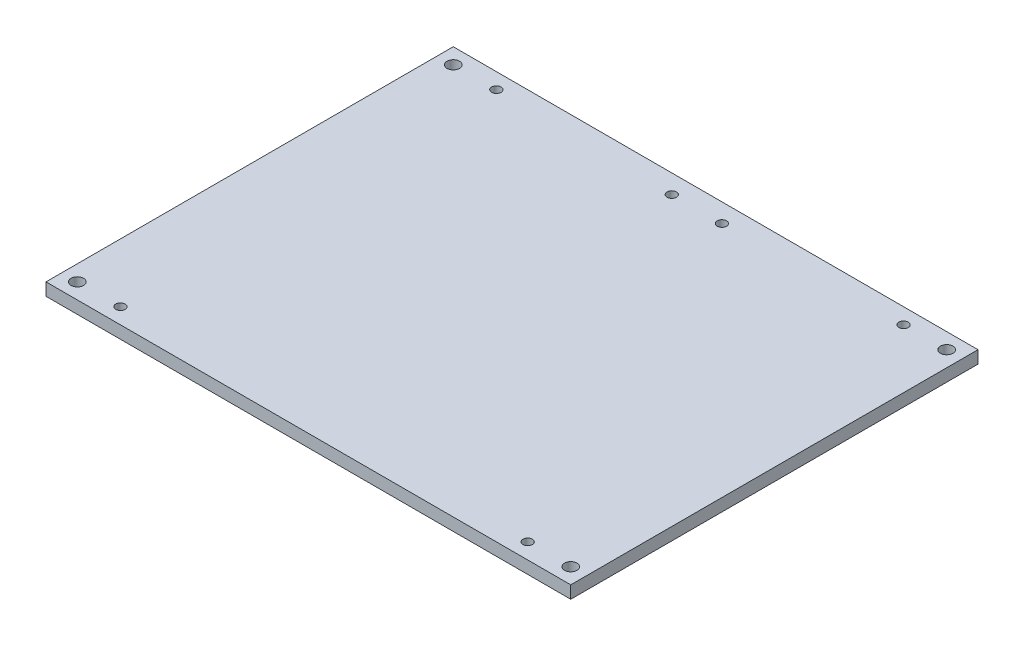
SolidWorks part; units mm, degrees
ref_plane "Front Plane" through (0, 0, 0) normal (0, 0, 1) x (1, 0, 0)
ref_plane "Top Plane" through (0, 0, 0) normal (0, 1, 0) x (1, 0, 0)
ref_plane "Right Plane" through (0, 0, 0) normal (1, 0, 0) x (0, 0, -1)
sketch "Sketch1" plane through (0, 0, 0) normal (0, 1, 0) x (1, 0, 0)
  line L1 (-83.75, 65) -> (83.75, 65)
  line L2 (-83.75, 65) -> (-83.75, -65)
  line L3 (-83.75, -65) -> (83.75, -65)
  line L4 (83.75, 65) -> (83.75, -65)
  line L5 (-83.75, 65) -> (83.75, -65) construction
  line L6 (-83.75, -65) -> (83.75, 65) construction
  point P0 (0, 0)
  dimension "D1" = 130
  dimension "D2" = 167.5
extrude "Boss-Extrude1" add sketch "Sketch1" along normal blind 4
sketch "Sketch2" plane through (0, 4, 0) normal (0, 1, 0) x (1, 0, 0)
  line L0 (-83.75, -65) -> (83.75, -65) construction
  line L1 (-65, 60) -> (65, 60) construction
  line L2 (-65, 60) -> (-65, -60) construction
  line L3 (-65, -60) -> (65, -60) construction
  line L4 (65, 60) -> (65, -60) construction
  line L5 (-65, 60) -> (65, -60) construction
  line L6 (-65, -60) -> (65, 60) construction
  circle A0 centre (-65, -60) radius 1.5
  circle A1 centre (65, -60) radius 1.5
  circle A2 centre (65, 60) radius 1.5
  circle A3 centre (-65, 60) radius 1.5
  point P0 (0, 0)
  dimension "D3" = 3
  dimension "D4" = 5
  dimension "D1" = 130
  dimension "D2" = 120
extrude "Cut-Extrude1" cut sketch "Sketch2" against normal blind 3
sketch "Sketch3" plane through (0, 4, 0) normal (0, 1, 0) x (1, 0, 0)
  line L0 (-8, 59) -> (8, 59) construction
  line L1 (83.75, 65) -> (-83.75, 65) construction
  circle A0 centre (-8, 59) radius 1.5
  circle A1 centre (8, 59) radius 1.5
  point P3 (0, 59)
  dimension "D2" = 3
  dimension "D1" = 16
  dimension "D3" = 6
extrude "Cut-Extrude2" cut sketch "Sketch3" against normal blind 3
sketch "Sketch4" plane through (0, 4, 0) normal (0, 1, 0) x (1, 0, 0)
  line L0 (-83.75, -65) -> (83.75, -65) construction
  line L1 (-30, 22) -> (30, 22)
  line L2 (-30, 22) -> (-30, 25)
  line L3 (-30, 25) -> (30, 25)
  line L4 (30, 22) -> (30, 25)
  line L5 (-30, -32) -> (30, -32)
  line L6 (-30, -32) -> (-30, -35)
  line L7 (-30, -35) -> (30, -35)
  line L8 (30, -32) -> (30, -35)
  point P8 (0, 22)
  dimension "D1" = 54
  dimension "D2" = 3
  dimension "D3" = 30
  dimension "D4" = 60
sketch "Sketch5" plane through (0, 4, 0) normal (0, 1, 0) x (1, 0, 0)
  line L1 (-78.75, -60) -> (78.75, -60) construction
  line L2 (-78.75, -60) -> (-78.75, 60) construction
  line L3 (-78.75, 60) -> (78.75, 60) construction
  line L4 (78.75, -60) -> (78.75, 60) construction
  line L5 (-78.75, -60) -> (78.75, 60) construction
  line L6 (-78.75, 60) -> (78.75, -60) construction
  circle A0 centre (-78.75, 60) radius 2
  circle A1 centre (78.75, 60) radius 2
  circle A2 centre (78.75, -60) radius 2
  circle A3 centre (-78.75, -60) radius 2
  point P0 (0, 0)
  dimension "D3" = 4
  dimension "D1" = 157.5
  dimension "D2" = 120
extrude "Cut-Extrude3" cut sketch "Sketch5" against normal blind 10
